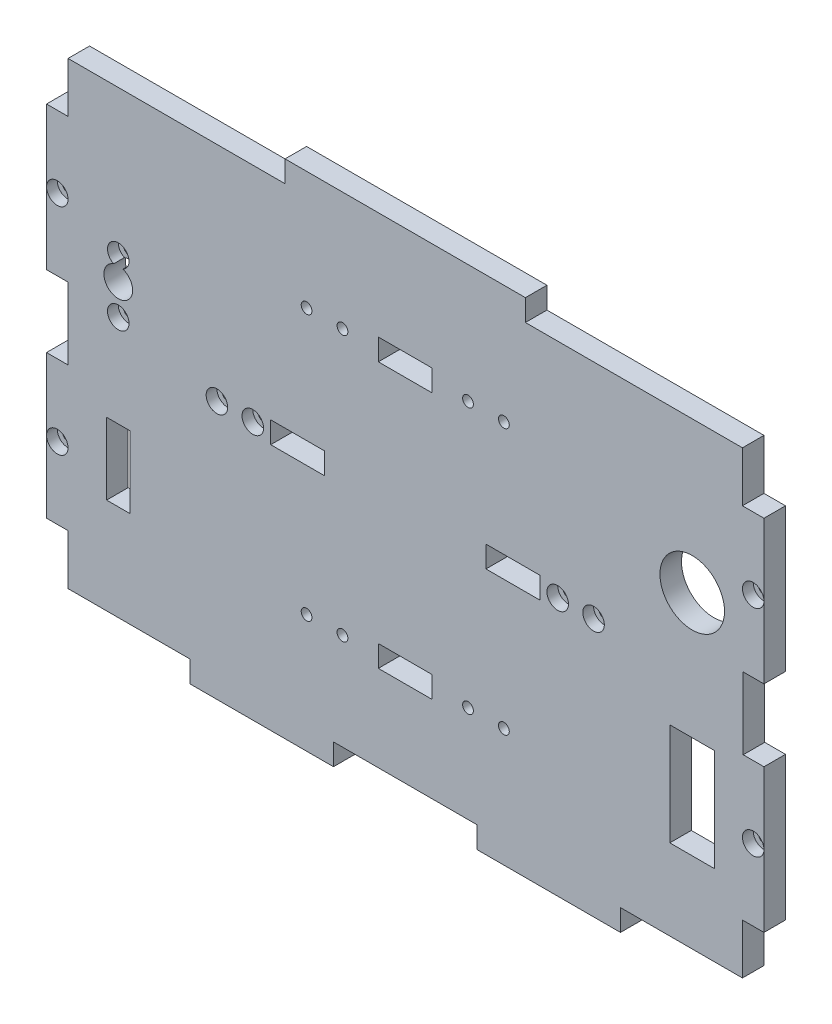
SolidWorks part; units mm, degrees
ref_plane "Plan de face" through (0, 0, 0) normal (0, 0, 1) x (1, 0, 0)
ref_plane "Plan de dessus" through (0, 0, 0) normal (0, 1, 0) x (1, 0, 0)
ref_plane "Plan de droite" through (0, 0, 0) normal (1, 0, 0) x (0, 0, -1)
sketch "Esquisse1" plane through (0, 0, 0) normal (0, 0, 1) x (1, 0, 0)
  line L1 (0, 0) -> (-200, 0)
  line L2 (0, 0) -> (0, 140)
  line L3 (0, 140) -> (-200, 140)
  line L4 (-200, 0) -> (-200, 140)
  dimension "D1" = 140
  dimension "D2" = 200
extrude "Boss.-Extru.1" add sketch "Esquisse1" along normal blind 6
sketch "Esquisse2" plane through (0, 0, 6) normal (0, 0, 1) x (1, 0, 0)
  line L0 (-200, 0) -> (0, 0) construction
  line L1 (-183.25, 52.75) -> (-176.75, 52.75)
  line L2 (-183.25, 52.75) -> (-183.25, 32.75)
  line L3 (-183.25, 32.75) -> (-176.75, 32.75)
  line L4 (-176.75, 52.75) -> (-176.75, 32.75)
  line L5 (-26.25, 28.5) -> (-13.75, 28.5)
  line L6 (-26.25, 28.5) -> (-26.25, 57)
  line L7 (-26.25, 57) -> (-13.75, 57)
  line L8 (-13.75, 28.5) -> (-13.75, 57)
  line L9 (0, 0) -> (0, 140) construction
  line L10 (-180, 0) -> (-180, 140) construction
  line L11 (0, 140) -> (-200, 140) construction
  line L12 (-200, 140) -> (-200, 0) construction
  line L14 (-100, 140) -> (-100, 109.3401) construction
  line L15 (-200, 70) -> (0, 70) construction
  line L16 (-20, 140) -> (-20, 0) construction
  circle A0 centre (-20, 92) radius 9
  circle A1 centre (-180, 87) radius 4
  dimension "D5" = 18
  dimension "D6" = 12.5
  dimension "D9" = 17
  dimension "D12" = 8
  dimension "D13" = 3.25
  dimension "D8" = 22
  dimension "D1" = 20
  dimension "D2" = 6.5
  dimension "D3" = 6.25
  dimension "D4" = 28.5
  dimension "D7" = 20
  dimension "D10" = 20
  dimension "D11" = 13
  dimension "D14" = 4.25
  dimension "D15" = 6.25
extrude "Enlèv. mat.-Extru.1" cut sketch "Esquisse2" against normal through all
sketch "Esquisse3" plane through (0, 0, 6) normal (0, 0, 1) x (1, 0, 0)
  line L0 (-200, 0) -> (0, 0) construction
  line L1 (-200, 0) -> (-160, 0)
  line L2 (-200, 0) -> (-200, 6)
  line L3 (-200, 6) -> (-160, 6)
  line L4 (-160, 0) -> (-160, 6)
  line L5 (-120, 0) -> (-80, 0)
  line L6 (-120, 0) -> (-120, 6)
  line L7 (-120, 6) -> (-80, 6)
  line L8 (-80, 0) -> (-80, 6)
  line L9 (0, 0) -> (0, 140) construction
  line L10 (-40, 0) -> (0, 0)
  line L11 (-40, 0) -> (-40, 6)
  line L12 (-40, 6) -> (0, 6)
  line L13 (0, 0) -> (0, 6)
  line L14 (-200, 70) -> (0, 70) construction
  line L15 (-200, 140) -> (-200, 0) construction
  line L16 (0, 140) -> (-200, 140) construction
  line L17 (-200, 140) -> (-133.5, 140)
  line L18 (-200, 140) -> (-200, 134)
  line L19 (-200, 134) -> (-133.5, 134)
  line L20 (-133.5, 140) -> (-133.5, 134)
  line L22 (-66.5, 140) -> (0, 140)
  line L23 (-66.5, 140) -> (-66.5, 134)
  line L24 (-66.5, 134) -> (0, 134)
  line L25 (0, 140) -> (0, 134)
  dimension "D1" = 40
  dimension "D2" = 6
  dimension "D3" = 40
  dimension "D4" = 40
  dimension "D5" = 40
  dimension "D6" = 6
  dimension "D7" = 6
  dimension "D14" = 66.5
  dimension "D15" = 6
  dimension "D16" = 0
  dimension "D17" = 66.5
  dimension "D18" = 6
  dimension "D19" = 67
extrude "Enlèv. mat.-Extru.2" cut sketch "Esquisse3" against normal blind 6
sketch "Esquisse7" plane through (0, 0, 6) normal (0, 0, 1) x (1, 0, 0)
  line L0 (-194, 6) -> (-194, 140)
  line L1 (-160, 6) -> (-200, 6) construction
  line L3 (-200, 134) -> (-200, 6) construction
  line L4 (-6, 6) -> (-6, 20)
  line L5 (0, 6) -> (-40, 6) construction
  line L6 (-6, 20) -> (0, 20)
  line L7 (0, 6) -> (0, 134) construction
  line L8 (0, 120) -> (-6, 120)
  line L9 (-6, 120) -> (-6, 134)
  line L11 (-66.5, 140) -> (-133.5, 140) construction
  line L12 (-6, 134) -> (0, 134)
  line L13 (0, 6) -> (0, 134) construction
  line L14 (-66.5, 140) -> (-133.5, 140) construction
  circle A0 centre (-3, 100) radius 1.5
  circle A1 centre (-3, 40) radius 1.5
  dimension "D6" = 3
  dimension "D7" = 3
  dimension "D1" = 6
  dimension "D2" = 6
  dimension "D3" = 14
  dimension "D4" = 20
  dimension "D5" = 6
  dimension "D8" = 20
  dimension "D9" = 20
  dimension "D10" = 3
  dimension "D11" = 3
  dimension "D12" = 14
extrude "Enlèv. mat.-Extru.4" cut sketch "Esquisse7" against normal blind 6
sketch "Esquisse9" plane through (0, 0, 6) normal (0, 0, 1) x (1, 0, 0)
  line L0 (0, 60) -> (-5.7852, 60)
  line L1 (0, 20) -> (0, 120) construction
  line L2 (-5.7852, 60) -> (-5.7852, 80)
  line L3 (-5.7852, 80) -> (0, 80)
  line L4 (0, 60) -> (0, 80)
  circle A0 centre (-3, 40) radius 1.5 construction
  circle A1 centre (-3, 100) radius 1.5 construction
  dimension "D1" = 20
  dimension "D2" = 20
  dimension "D3" = 20
extrude "Enlèv. mat.-Extru.5" cut sketch "Esquisse9" against normal blind 6
sketch "Esquisse12" plane through (0, 0, 6) normal (0, 0, 1) x (1, 0, 0)
  line L0 (-194, 6) -> (-194, 134) construction
  line L1 (-194, 120) -> (-200, 120)
  line L2 (-194, 120) -> (-194, 80)
  line L3 (-194, 80) -> (-200, 80)
  line L4 (-200, 120) -> (-200, 80)
  line L5 (-160, 6) -> (-194, 6) construction
  line L6 (-194, 60) -> (-200, 60)
  line L7 (-194, 60) -> (-194, 20)
  line L8 (-194, 20) -> (-200, 20)
  line L9 (-200, 60) -> (-200, 20)
  dimension "D1" = 6
  dimension "D2" = 6
  dimension "D3" = 40
  dimension "D4" = 40
  dimension "D5" = 20
  dimension "D6" = 14
extrude "Boss.-Extru.2" add sketch "Esquisse12" against normal blind 6
sketch "Esquisse13" plane through (0, 0, 6) normal (0, 0, 1) x (1, 0, 0)
  line L0 (-200, 120) -> (-200, 80) construction
  line L1 (-194, 120) -> (-200, 120) construction
  line L2 (-200, 60) -> (-200, 20) construction
  line L3 (-200, 20) -> (-194, 20) construction
  circle A0 centre (-197, 100) radius 1.5
  circle A1 centre (-197, 40) radius 1.5
  dimension "D1" = 3
  dimension "D2" = 3
  dimension "D3" = 3
  dimension "D4" = 20
  dimension "D5" = 3
  dimension "D6" = 20
extrude "Enlèv. mat.-Extru.7" cut sketch "Esquisse13" against normal blind 6
sketch "Esquisse14" plane through (0, 0, 6) normal (0, 0, 1) x (1, 0, 0)
  line L0 (-100, 140) -> (-100, 6) construction
  line L1 (-77.5, 75) -> (-77.5, 69)
  line L2 (-62.5, 69) -> (-77.5, 69)
  line L3 (-62.5, 75) -> (-62.5, 69)
  line L4 (-62.5, 75) -> (-77.5, 75)
  line L5 (-137.5, 75) -> (-122.5, 75)
  line L6 (-137.5, 75) -> (-137.5, 69)
  line L7 (-137.5, 69) -> (-122.5, 69)
  line L8 (-122.5, 75) -> (-122.5, 69)
  line L13 (-66.5, 140) -> (-133.5, 140) construction
  line L14 (-80, 6) -> (-120, 6) construction
  line L16 (-200, 40) -> (0, 40) construction
  line L17 (-200, 60) -> (-200, 20) construction
  line L18 (0, 20) -> (0, 60) construction
  line L19 (-200, 75) -> (0, 75) construction
  circle A0 centre (-152.5, 72) radius 1.5
  circle A1 centre (-142.5, 72) radius 1.5
  circle A2 centre (-57.5, 72) radius 1.5
  circle A3 centre (-47.5, 72) radius 1.5
  dimension "D10" = 3
  dimension "D3" = 3
  dimension "D1" = 6
  dimension "D2" = 22.5
  dimension "D4" = 65
  dimension "D5" = 5
  dimension "D6" = 3
  dimension "D7" = 15
  dimension "D8" = 15
  dimension "D9" = 3
extrude "Enlèv. mat.-Extru.8" cut sketch "Esquisse14" against normal through all
sketch "Esquisse15" plane through (0, 0, 6) normal (0, 0, 1) x (1, 0, 0)
  line L1 (-180, 96.5856) -> (-180, 70.9414) construction
  line L4 (-180, 78.5) -> (-180, 93.5) construction
  circle A2 centre (-180, 93.5) radius 1.5
  circle A3 centre (-180, 78.5) radius 1.5
  circle A4 centre (-180, 87) radius 4 construction
  dimension "D8" = 3
  dimension "D9" = 3
  dimension "D11" = 8.5
  dimension "D10" = 6.5
extrude "Enlèv. mat.-Extru.9" cut sketch "Esquisse15" against normal through all
sketch "Esquisse17" plane through (0, 0, 6) normal (0, 0, 1) x (1, 0, 0)
  circle A0 centre (-180, 93.5) radius 3
  circle A1 centre (-180, 78.5) radius 3
  dimension "D1" = 6
  dimension "D2" = 6
extrude "Enlèv. mat.-Extru.12" cut sketch "Esquisse17" against normal blind 3
sketch "Esquisse18" plane through (0, 0, 6) normal (0, 0, 1) x (1, 0, 0)
  line L1 (-107.5, 110) -> (-92.5, 110)
  line L2 (-107.5, 110) -> (-107.5, 104)
  line L3 (-107.5, 104) -> (-92.5, 104)
  line L4 (-92.5, 110) -> (-92.5, 104)
  line L5 (-107.5, 36) -> (-92.5, 36)
  line L6 (-107.5, 36) -> (-107.5, 30)
  line L7 (-107.5, 30) -> (-92.5, 30)
  line L8 (-92.5, 36) -> (-92.5, 30)
  line L10 (-194, 70) -> (-5.7852, 70) construction
  line L11 (-194, 60) -> (-194, 80) construction
  line L12 (-5.7852, 80) -> (-5.7852, 60) construction
  line L13 (-100, 140) -> (-100, 6) construction
  line L14 (-66.5, 140) -> (-133.5, 140) construction
  line L15 (-80, 6) -> (-120, 6) construction
  circle A0 centre (-117.5, 107) radius 1.5
  circle A1 centre (-82.5, 107) radius 1.5
  circle A2 centre (-117.5, 33) radius 1.5
  circle A3 centre (-82.5, 33) radius 1.5
  circle A4 centre (-127.5, 107) radius 1.5
  circle A5 centre (-72.5, 107) radius 1.5
  circle A6 centre (-72.5, 33) radius 1.5
  circle A7 centre (-127.5, 33) radius 1.5
  dimension "D11" = 3
  dimension "D13" = 3
  dimension "D1" = 68
  dimension "D2" = 7.5
  dimension "D3" = 6
  dimension "D4" = 6
  dimension "D5" = 15
  dimension "D6" = 15
  dimension "D7" = 7.5
  dimension "D8" = 34
  dimension "D9" = 10
  dimension "D10" = 3
  dimension "D12" = 10
  dimension "D14" = 3
extrude "Enlèv. mat.-Extru.13" cut sketch "Esquisse18" against normal through all
sketch "Esquisse20" plane through (0, 0, 6) normal (0, 0, 1) x (1, 0, 0)
  line L0 (-92.5, 110) -> (-107.5, 110) construction
  line L1 (-140, 110) -> (-60, 110)
  line L2 (-140, 110) -> (-140, 30) construction
  line L3 (-140, 30) -> (-60, 30)
  line L4 (-60, 110) -> (-60, 30)
  line L5 (-107.5, 110) -> (-107.5, 104) construction
  dimension "D1" = 0
  dimension "D2" = 80
  dimension "D3" = 32.5
  dimension "D4" = 80
sketch "Esquisse16" plane through (0, 0, 6) normal (0, 0, 1) x (1, 0, 0)
  line L0 (-100, 140) -> (-100, 6) construction
  line L1 (-66.5, 140) -> (-133.5, 140) construction
  line L2 (-80, 6) -> (-120, 6) construction
  circle A0 centre (-197, 100) radius 2.995
  circle A1 centre (-142.5, 72) radius 3
  circle A2 centre (-152.5, 72) radius 3
  circle A3 centre (-57.5, 72) radius 3
  circle A7 centre (-197, 40) radius 2.995
  circle A8 centre (-3, 40) radius 2.995
  circle A13 centre (-47.5, 72) radius 3
  circle A15 centre (-3, 100) radius 2.995
  dimension "D2" = 6
  dimension "D3" = 6
  dimension "D5" = 6
  dimension "D7" = 5.99
  dimension "D10" = 5.99
extrude "Enlèv. mat.-Extru.11" cut sketch "Esquisse16" against normal blind 3
